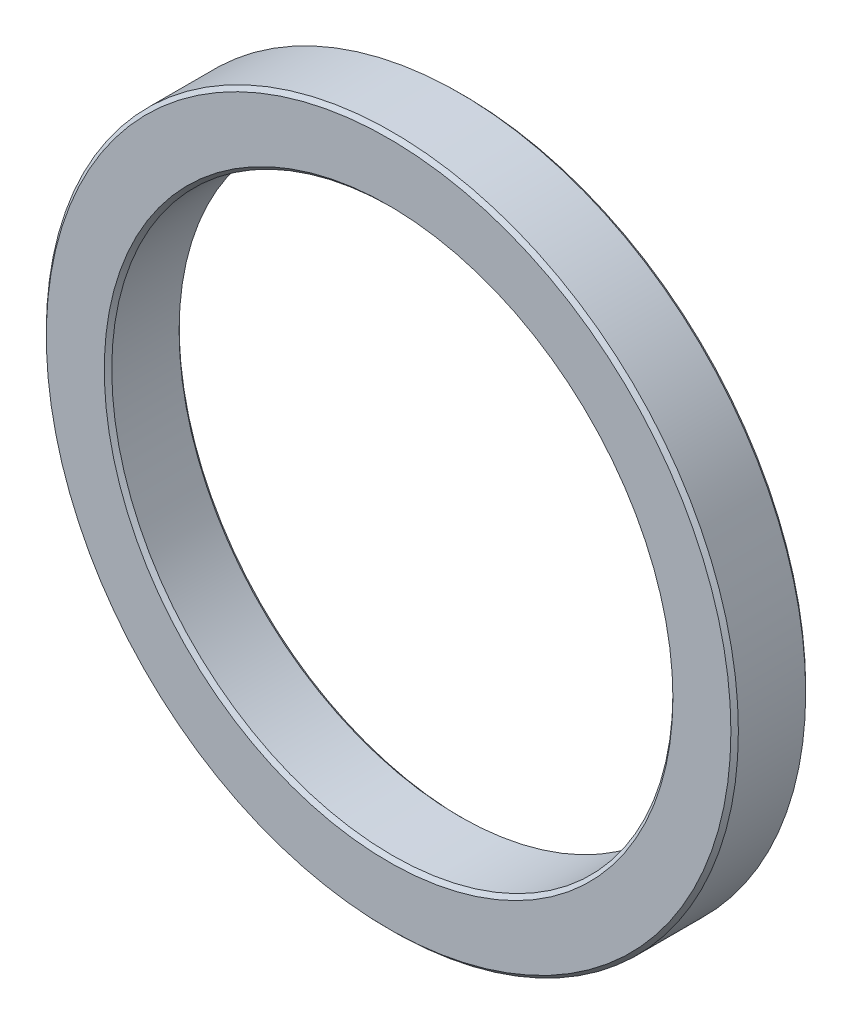
SolidWorks part; units mm, degrees
ref_plane "前视基准面" through (0, 0, 0) normal (0, 0, 1) x (1, 0, 0)
ref_plane "上视基准面" through (0, 0, 0) normal (0, 1, 0) x (1, 0, 0)
ref_plane "右视基准面" through (0, 0, 0) normal (1, 0, 0) x (0, 0, -1)
other "Configuration Table"
sketch "草图1" plane through (0, 0, 0) normal (0, 0, 1) x (1, 0, 0)
  circle A0 centre (0, 0) radius 18.5
  circle A1 centre (0, 0) radius 15
  dimension "D1" = 37
  dimension "D2" = 30
extrude "凸台-拉伸1" add sketch "草图1" along normal blind 4
chamfer "倒角1" distance 0.2 angle 45 4 edges at (15, 0, 0) (18.5, 0, 0) (15, 0, 4) (18.5, 0, 4)
